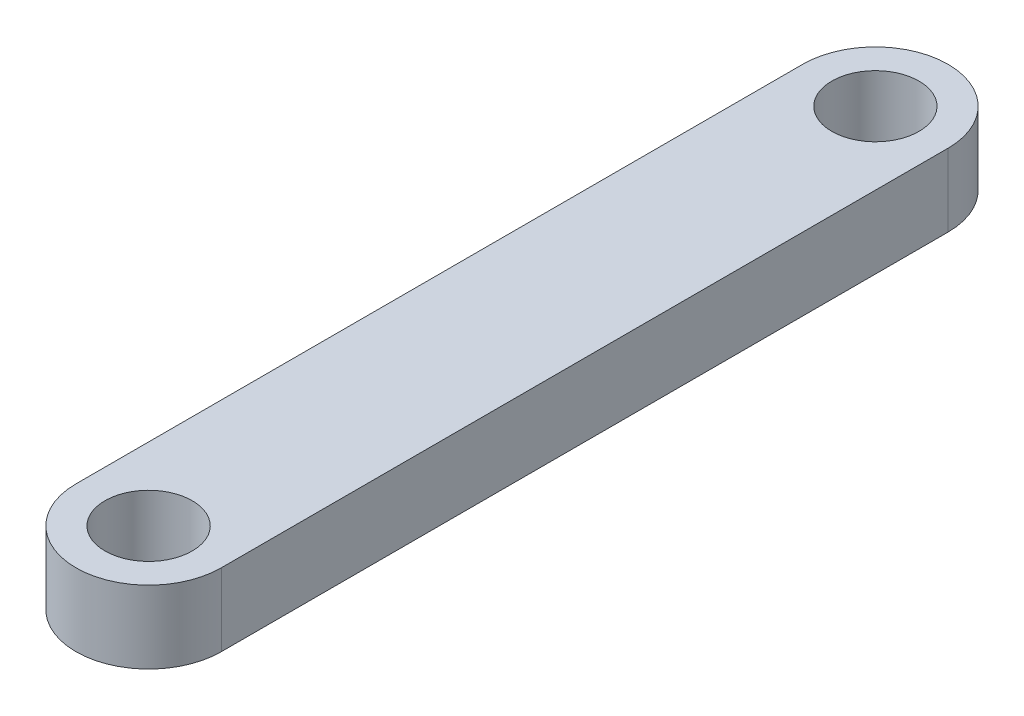
SolidWorks part; units mm, degrees
ref_plane "Front Plane" through (0, 0, 0) normal (0, 0, 1) x (1, 0, 0)
ref_plane "Top Plane" through (0, 0, 0) normal (0, 1, 0) x (1, 0, 0)
ref_plane "Right Plane" through (0, 0, 0) normal (1, 0, 0) x (0, 0, -1)
sketch "Sketch1" plane through (0, 0, 0) normal (0, 1, 0) x (1, 0, 0)
  line L0 (0, 0) -> (0, 100) construction
  line L1 (10, 0) -> (10, 100)
  line L2 (-10, 0) -> (-10, 100)
  arc A0 (10, 0) -> (-10, 0) centre (0, 0) cw
  arc A1 (10, 100) -> (-10, 100) centre (0, 100) ccw
  circle A2 centre (0, 100) radius 6
  circle A3 centre (0, 0) radius 6
  dimension "D4" = 12
  dimension "D3" = 100
  dimension "D1" = 10
  dimension "D2" = 10
extrude "Boss-Extrude1" add sketch "Sketch1" along normal blind 10
